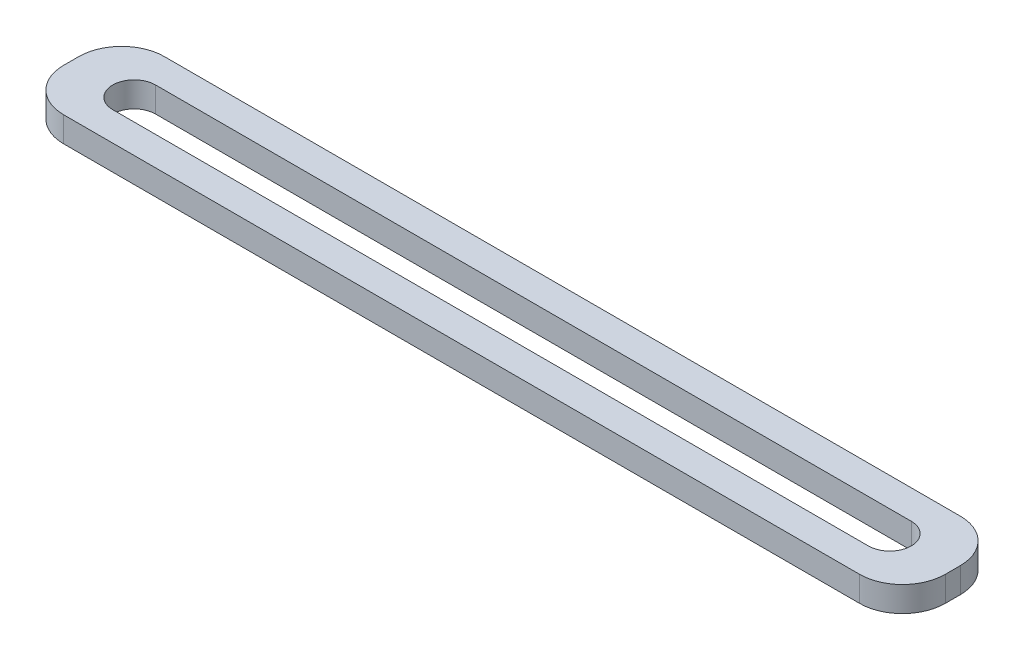
SolidWorks part; units mm, degrees
ref_plane "前视基准面" through (0, 0, 0) normal (0, 0, 1) x (1, 0, 0)
ref_plane "上视基准面" through (0, 0, 0) normal (0, 1, 0) x (1, 0, 0)
ref_plane "右视基准面" through (0, 0, 0) normal (1, 0, 0) x (0, 0, -1)
other "Configuration Table"
sketch "草图1" plane through (0, 0, 0) normal (0, 1, 0) x (1, 0, 0)
  line L0 (-20, 0) -> (20, 0) construction
  line L5 (-25, 4) -> (25, -4) construction
  line L6 (-25, -4) -> (25, 4) construction
  line L11 (-20, 1.7) -> (20, -1.7) construction
  line L12 (-20, -1.7) -> (20, 1.7) construction
  line L14 (-35, 4) -> (35, 4)
  line L15 (-35, 4) -> (-35, -4)
  line L16 (-35, -4) -> (35, -4)
  line L17 (35, 4) -> (35, -4)
  line L18 (-35, 4) -> (35, -4) construction
  line L19 (-35, -4) -> (35, 4) construction
  line L20 (-30, 1.7) -> (30, 1.7)
  line L21 (-30, 1.7) -> (-30, -1.7)
  line L22 (-30, -1.7) -> (30, -1.7)
  line L23 (30, 1.7) -> (30, -1.7)
  line L25 (-30, -1.7) -> (30, 1.7) construction
  circle A2 centre (30, 0) radius 1.7
  circle A3 centre (-30, 0) radius 1.7
  point P0 (0, 0)
  point P5 (0, 0)
  point P15 (0, 0)
  point P20 (0, 0)
  dimension "D5" = 8
  dimension "D1" = 8
  dimension "D2" = 50
  dimension "D3" = 3.4
  dimension "D4" = 40
  dimension "D6" = 70
  dimension "D7" = 3.4
  dimension "D8" = 60
extrude "凸台-拉伸1" add sketch "草图1" along normal blind 2 contours L17 L14 L15 L16 A3 L20 A2 L22
fillet "圆角1" radius 3.4 4 edges at (35, 1, 4) (35, 1, -4) (-35, 1, 4) (-35, 1, -4)
